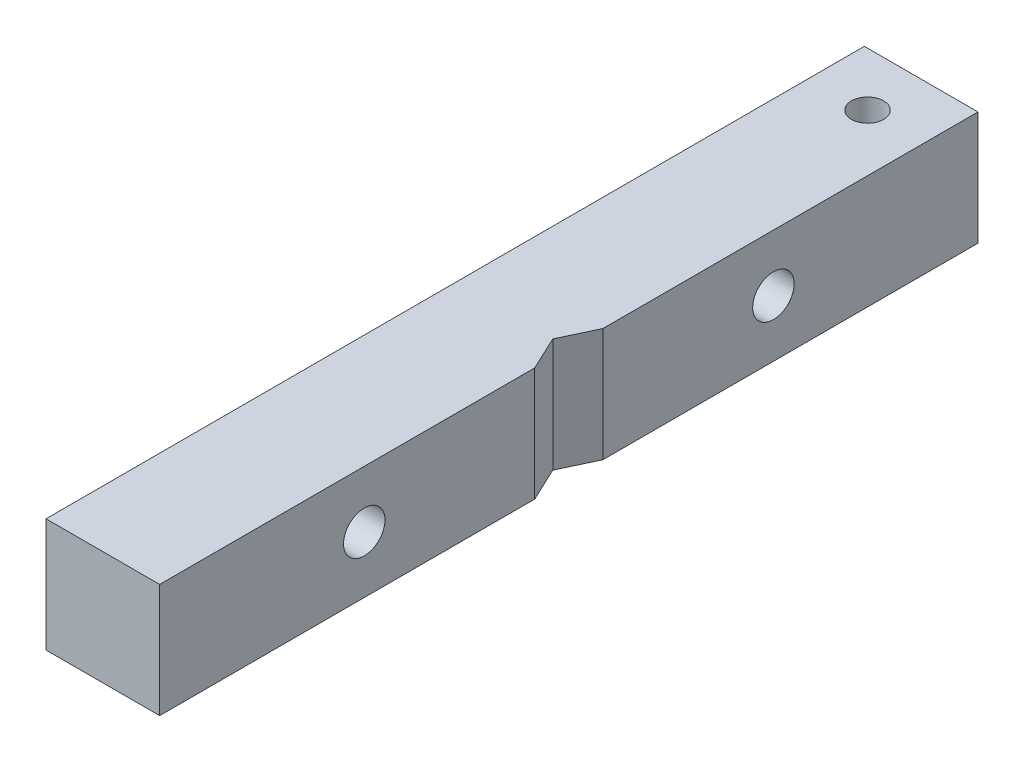
SolidWorks part; units mm, degrees
ref_plane "Front Plane" through (0, 0, 0) normal (0, 0, 1) x (1, 0, 0)
ref_plane "Top Plane" through (0, 0, 0) normal (0, 1, 0) x (1, 0, 0)
ref_plane "Right Plane" through (0, 0, 0) normal (1, 0, 0) x (0, 0, -1)
sketch "Sketch1" plane through (0, 0, 0) normal (0, 0, 1) x (1, 0, 0)
  line L1 (7.9375, -7.9375) -> (-7.9375, -7.9375)
  line L2 (7.9375, -7.9375) -> (7.9375, 7.9375)
  line L3 (7.9375, 7.9375) -> (-7.9375, 7.9375)
  line L4 (-7.9375, -7.9375) -> (-7.9375, 7.9375)
  line L5 (7.9375, -7.9375) -> (-7.9375, 7.9375) construction
  line L6 (7.9375, 7.9375) -> (-7.9375, -7.9375) construction
  point P0 (0, 0)
  dimension "D1" = 15.875
  dimension "D2" = 15.875
extrude "Boss-Extrude1" add sketch "Sketch1" along normal mid plane 114.3
sketch "Sketch2" plane through (0, 7.9375, 0) normal (0, 1, 0) x (1, 0, 0)
  line L0 (7.9375, 4.7625) -> (5.6999, 0)
  line L1 (7.9375, -57.15) -> (7.9375, 57.15) construction
  line L2 (5.6999, 0) -> (7.9375, -4.7625)
  line L3 (0, 0) -> (5.6999, 0) construction
  dimension "D1" = 9.525
extrude "Cut-Extrude1" cut sketch "Sketch2" against normal through all and the other way through all
hole_wizard "#12 Clearance Hole1" positions "Sketch5" profile "Sketch4" hole size "#12" standard "ANSI Inch"
sketch "Sketch5" plane through (7.9375, 0, 0) normal (1, 0, 0) x (0, 0, -1)
  line L0 (57.15, -7.9375) -> (57.15, 7.9375) construction
  line L1 (-57.15, -7.9375) -> (-57.15, 7.9375) construction
  point P0 (28.575, 0)
  point P5 (-28.575, 0)
  dimension "D1" = 28.575
  dimension "D2" = 28.575
sketch "Sketch4" plane through (7.9375, 0, -28.575) normal (0, 1, 0) x (0, 0, -1)
  line L0 (0, 0) -> (0, 43.8099)
  line L1 (0, 43.8099) -> (2.8956, 42.07)
  line L2 (2.8956, 42.07) -> (2.8956, 0)
  line L5 (2.8956, 0) -> (0, 0)
  line L10 (0, 43.8099) -> (-2.8956, 42.07) construction
  line L11 (0, -6.35) -> (0, 107.95) construction
  dimension "Hole Dia." = 5.7912
  dimension "Hole Depth" = 42.07
  dimension "Drill Angle" = 118
hole_wizard "#12-24 Tapped Hole1" positions "Sketch6" profile "Sketch7" tap size "#12-24" standard "ANSI Inch" end condition through all
sketch "Sketch6" plane through (0, -7.9375, 0) normal (0, -1, 0) x (-1, 0, 0)
  point P0 (0, 49.6536)
sketch "Sketch7" plane through (0, -7.9375, -49.6536) normal (1, 0, 0) x (0, 0, -1)
  line L0 (0, 0) -> (0, 15.875)
  line L1 (0, 15.875) -> (2.2479, 15.875)
  line L2 (2.2479, 15.875) -> (2.2479, 0)
  line L5 (2.2479, 0) -> (0, 0)
  line L11 (0, -6.35) -> (0, 107.95) construction
  dimension "Thru Tap Drill Dia." = 4.4958
  dimension "Thru Tap Drill Depth" = 15.875
cosmetic thread "Hole Thread1" parameters "D2"=5.4864
